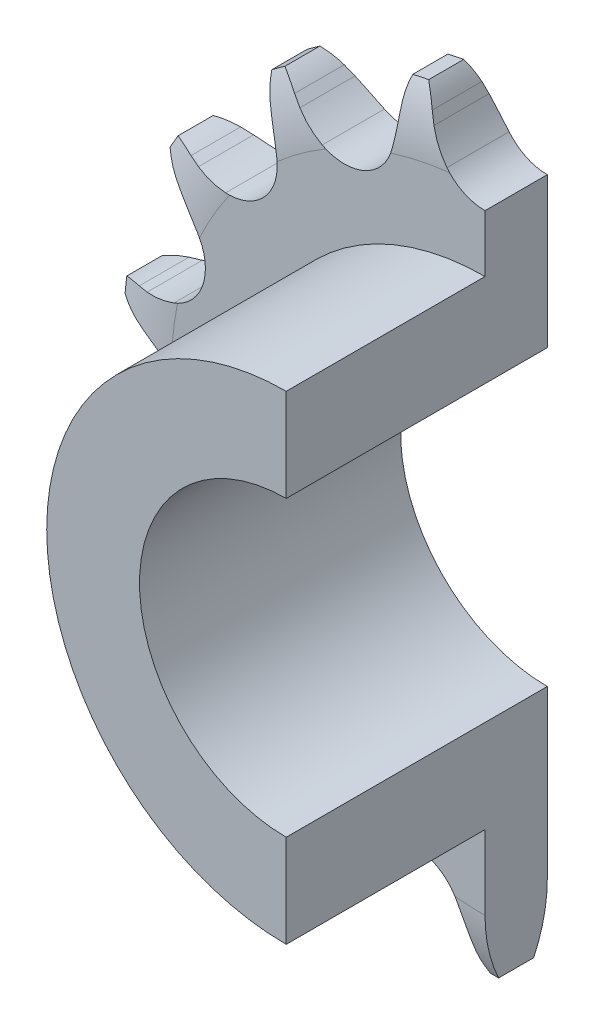
SolidWorks part; units mm, degrees
ref_plane "Front Plane" through (0, 0, 0) normal (0, 0, 1) x (1, 0, 0)
ref_plane "Top Plane" through (0, 0, 0) normal (0, 1, 0) x (1, 0, 0)
ref_plane "Right Plane" through (0, 0, 0) normal (1, 0, 0) x (0, 0, -1)
sketch "Sketch0" plane through (0, 0, 0) normal (0, 0, 1) x (1, 0, 0)
  line L0 (3, -14.1139) -> (0, 0) construction
  line L1 (0, 0) -> (8.4813, -11.6735) construction
  line L2 (0, 0) -> (-3, -14.1139) construction
  line L3 (3, -14.1139) -> (8.4813, -11.6735) construction
  line L4 (3, -14.1139) -> (-3, -14.1139) construction
  line L5 (5.4587, -13.8191) -> (5.1921, -13.4619)
  line L6 (3, -14.1139) -> (0, -14.7516) construction
  line L7 (0.6339, -14.8447) -> (0.7322, -14.4099)
  line L8 (0, -14.1139) -> (0, -15.9139) construction
  line L9 (4.2889, -12.5222) -> (0.9862, -16.6008) construction
  line L10 (0, 0) -> (0, -14.1139) construction
  line L11 (5.1921, -13.4619) -> (0.9862, -16.6008) construction
  line L12 (0, -15.9139) -> (0, -16.1712) construction
  line L13 (8.1159, -11.8362) -> (5.4587, -13.8191) construction
  circle A0 centre (0, 0) radius 15.9139 construction
  circle A1 centre (0, 0) radius 14.4292 construction
  arc A2 (-3.2007, -17.3745) -> (9.9908, -14.5706) centre (0, 0) ccw
  circle A3 centre (0, 0) radius 16.1712 construction
  circle A4 centre (3, -14.1139) radius 2 construction
  arc A7 (4.2889, -12.5222) -> (1.1751, -13.1841) centre (3, -14.1139) ccw
  circle A8 centre (3, -14.1139) radius 2.0481 construction
  arc A9 (5.4587, -13.8191) -> (9.9908, -14.5706) centre (8.1159, -11.8362) ccw
  arc A10 (5.1921, -13.4619) -> (4.2889, -12.5222) centre (0.9862, -16.6008) ccw
  arc A11 (0.6339, -14.8447) -> (-3.2007, -17.3745) centre (-2.6, -14.1139) cw
  arc A12 (0.7322, -14.4099) -> (1.1751, -13.1841) centre (5.8512, -15.5667) cw
  dimension "D1" = 2.0481
  dimension "R" = 2.0481
sketch "Sketch1" plane through (0, 0, 0) normal (1, 0, 0) x (0, 0, -1)
  line L0 (1.3, 0) -> (-1.3, 0)
  line L1 (-1.3, 0) -> (-1.3, 13.1014)
  line L2 (-1.3, 14.4292) -> (0, 14.4292) construction
  line L3 (-0.6, 15.9139) -> (0.6, 15.9139)
  line L5 (1.3, 13.1014) -> (1.3, 0)
  line L7 (0, 15.9139) -> (0, 0) construction
  line L8 (-1.3, 13.1014) -> (1.3, 13.1014) construction
  line L9 (0, 15.9139) -> (0, -15.9139) construction
  line L10 (-1.3, 13.1014) -> (-1.3, 15.9139) construction
  line L11 (-1.3, 15.9139) -> (-0.6, 15.9139) construction
  line L12 (0.6, 15.9139) -> (1.3, 15.9139) construction
  line L13 (1.3, 15.9139) -> (1.3, 13.1014) construction
  line L14 (0, 0) -> (-6.4008, 0) construction
  line L15 (-1.3, 14.4292) -> (-1.3, 10.3292) construction
  line L22 (1.3, 0) -> (-8.7, 0) construction
  line L24 (-1.3, 0) -> (-1.3, 10.3292) construction
  arc A0 (-0.6, 15.9139) -> (-1.3, 13.1014) centre (4.7, 13.1014) ccw
  arc A1 (0.6, 15.9139) -> (1.3, 13.1014) centre (-4.7, 13.1014) cw
  dimension "R" = 6
revolve "Revolve1" add sketch "Sketch1" angle 360 mid plane about L0
extrude "Cut-Extrude1" cut sketch "Sketch0" against normal through all and the other way through all
pattern_circular "CirPattern1" count 15 over 360 about axis through (0, 0, 0) along (0, 0, 1) of "Cut-Extrude1"
sketch "Sketch2" plane through (0, 0, 0) normal (0, 0, 1) x (1, 0, 0)
  circle A0 centre (0, 0) radius 3 construction
  circle A1 centre (0, 0) radius 10
  circle A2 centre (0, 0) radius 15.65 construction
  dimension "Bore" = 6
  dimension "Hub Dia." = 20
  dimension "OD" = 31.3
extrude "Boss-Extrude1" add sketch "Sketch2" along normal up to vertex (8.7 mm away) from surface at 1.3 starting at face at (0, 0, 1.3)
sketch "Sketch3" plane through (0, 0, 0) normal (0, 0, 1) x (1, 0, 0)
  circle A0 centre (0, 0) radius 3 construction
  circle A1 centre (0, 0) radius 3
extrude "Cut-Extrude2" cut sketch "Sketch3" along normal through all and the other way through all
sketch "Sketch4" plane through (0, 0, 0) normal (1, 0, 0) x (0, 0, -1)
  line L0 (-8.7, 10) -> (-8.7, 9.5)
  line L1 (-1.3, 15.9139) -> (-3.25, 15.9139)
  line L2 (-1.3, 15.9139) -> (-1.3, 10.3292)
  line L3 (-1.3, 10.3292) -> (-3.25, 10.3292)
  line L4 (-3.25, 15.9139) -> (-3.25, 10.3292)
  line L9 (-8.7, 9.5) -> (-8.2, 10)
  line L10 (-8.2, 10) -> (-8.7, 10)
  dimension "C" = 0.5
  dimension "D3" = 1.95
revolve "Cut-Revolve1" cut sketch "Sketch4" angle 360 mid plane about L22
sketch "Sketch5" plane through (0, 0, 0) normal (0, 0, 1) x (1, 0, 0)
  circle A0 centre (0, 0) radius 15.65 construction
  circle A1 centre (0, 0) radius 15.65
extrude "Cut-Extrude3" cut sketch "Sketch5" against normal through all and the other way through all flip side to cut
sketch "Sketch6" plane through (0, 0, 0) normal (0, 0, 1) x (1, 0, 0)
  circle A0 centre (0, 0) radius 10
  dimension "D1" = 20
extrude "Cut-Extrude4" cut sketch "Sketch6" against normal through all both and the other way through all
sketch "Sketch7" plane through (0, 0, 1.3) normal (0, 0, 1) x (1, 0, 0)
  circle A0 centre (0, 0) radius 10
  circle A2 centre (0, 0) radius 6.125
  dimension "D1" = 20
  dimension "D2" = 12.25
extrude "Boss-Extrude2" add sketch "Sketch7" along normal blind 8.3 and the other way up to surface (2.6 mm away) other way up to face at (0, 10, -1.3)
sketch "Sketch8" plane through (0, 0, 0) normal (0, 0, 1) x (1, 0, 0)
  line L0 (0, 20.8664) -> (0, -21.8881) construction
  line L2 (0, 18.377) -> (20.3504, 18.377)
  line L3 (0, 18.377) -> (0, -18.0918)
  line L4 (0, -18.0918) -> (20.3504, -18.0918)
  line L5 (20.3504, 18.377) -> (20.3504, -18.0918)
extrude "Cut-Extrude5" cut sketch "Sketch8" against normal through all both and the other way through all
equation "\"360/N@Sketch0\" = 360/\"Teeth@CirPattern1\""
equation "\"Ds@Sketch0\" = 1.005 * \"Dr@Sketch0\" + ( 0.003 * 25.4 ) "
equation "\"R@Sketch0\" = 1/2 * \"Ds@Sketch0\""
equation "\"A@Sketch0\" = 35 +  ( 60 / \"Teeth@CirPattern1\" ) "
equation "\"B@Sketch0\" = 18 -  ( 56 / \"Teeth@CirPattern1\" )"
equation "\"ac@Sketch0\" = 0.8 * \"Dr@Sketch0\""
equation "\"ab@Sketch0\" = 1.4 * \"Dr@Sketch0\""
equation "\"J@Sketch0\" = 0.3 * \"Pitch@Sketch0\""
equation "\"D3@Sketch4\" = \"t@Sketch1\" * 3 / 4"
